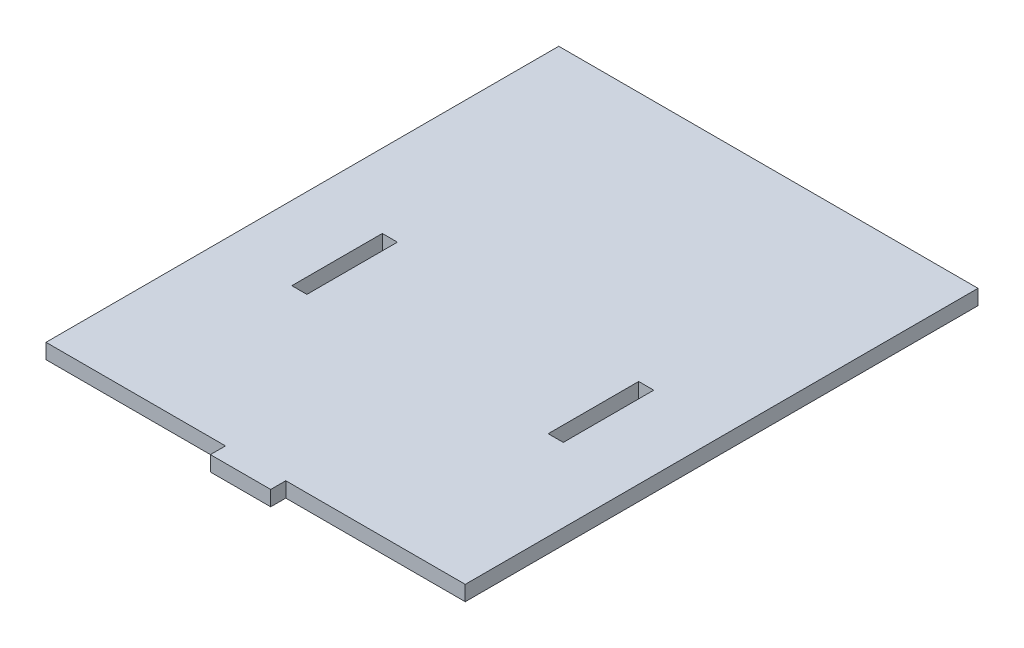
SolidWorks part; units mm, degrees
ref_plane "Front Plane" through (0, 0, 0) normal (0, 0, 1) x (1, 0, 0)
ref_plane "Top Plane" through (0, 0, 0) normal (0, 1, 0) x (1, 0, 0)
ref_plane "Right Plane" through (0, 0, 0) normal (1, 0, 0) x (0, 0, -1)
sketch "Sketch1" plane through (0, 0, 0) normal (0, 1, 0) x (1, 0, 0)
  line L1 (-61.25, 98) -> (61.25, 98)
  line L3 (-45, -72) -> (-10, -72)
  line L5 (-61.25, 98) -> (45, -72) construction
  line L6 (-45, -72) -> (61.25, 98) construction
  line L11 (10, -72) -> (45, -72)
  line L14 (45, 15) -> (40, 15)
  line L15 (40, 15) -> (40, -15)
  line L16 (40, -15) -> (45, -15)
  line L17 (0, -55) -> (0, 55) construction
  line L18 (-40, 15) -> (-40, -15)
  line L19 (-45, 15) -> (-40, 15)
  line L20 (-40, -15) -> (-45, -15)
  line L23 (-10, -72) -> (10, -72)
  line L24 (-45, 15) -> (-45, -15)
  line L25 (45, 15) -> (45, -15)
  line L26 (-45, -72) -> (-69.5, -72)
  line L27 (-69.5, -72) -> (-69.5, 98)
  line L28 (-69.5, 98) -> (-61.25, 98)
  line L29 (45, -72) -> (69.5, -72)
  line L30 (69.5, -72) -> (69.5, 98)
  line L31 (69.5, 98) -> (61.25, 98)
  line L32 (-10, -72) -> (-10, -77)
  line L33 (-10, -77) -> (10, -77)
  line L34 (10, -77) -> (10, -72)
  point P0 (0, 0)
  dimension "D1" = 170
  dimension "D2" = 90
  dimension "D3" = 24.5
  dimension "D4" = 24.5
  dimension "D5" = 5
  dimension "D6" = 5
  dimension "D7" = 30
extrude "Boss-Extrude1" add sketch "Sketch1" along normal blind 5 contours L30 L31 L1 L28 L27 L26 L3 L23 L11 L29 L14 L25 L16 L15 L24 L19 L18 L20 | L33 L34 L23 L32
